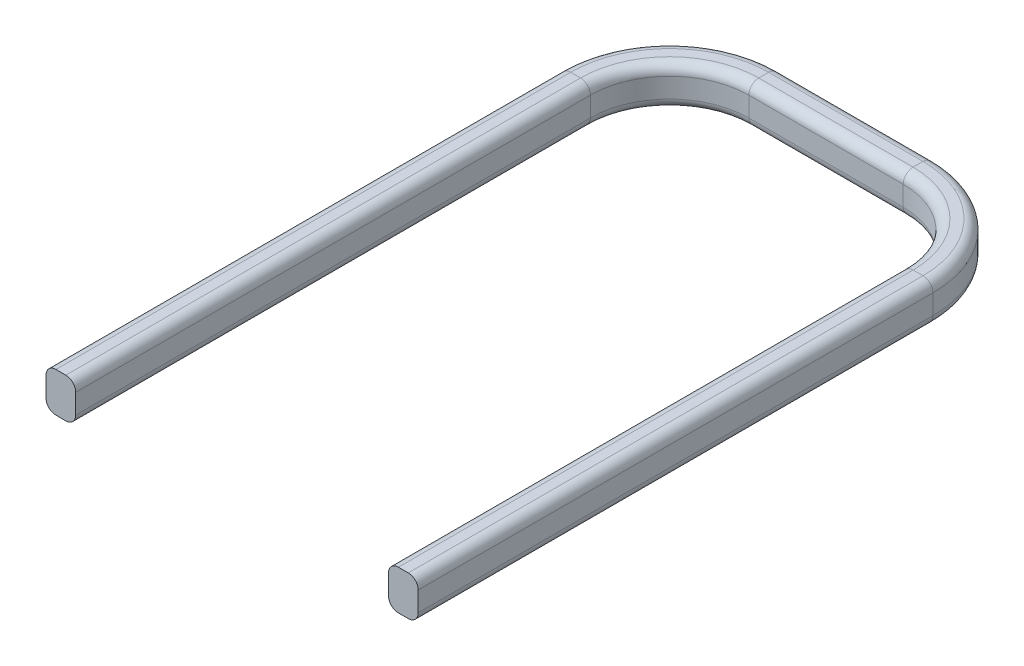
SolidWorks part; units mm, degrees
ref_plane "Front Plane" through (0, 0, 0) normal (0, 0, 1) x (1, 0, 0)
ref_plane "Top Plane" through (0, 0, 0) normal (0, 1, 0) x (1, 0, 0)
ref_plane "Right Plane" through (0, 0, 0) normal (1, 0, 0) x (0, 0, -1)
sketch "Sketch1" plane through (0, 0, 0) normal (0, 1, 0) x (1, 0, 0)
  line L0 (-3.95, 0) -> (-3.95, 13)
  line L1 (-1.95, 15) -> (1.95, 15)
  line L2 (3.95, 13) -> (3.95, 0)
  arc A0 (3.95, 13) -> (1.95, 15) centre (1.95, 13) ccw
  arc A1 (-1.95, 15) -> (-3.95, 13) centre (-1.95, 13) ccw
  point P4 (0, 0)
  point P5 (0, 0)
  point P7 (0, 0)
  point P8 (0, 0)
  point P9 (0, 15)
  point P10 (0, 0)
  point P15 (-3.95, 15)
  dimension "D3" = 2
  dimension "D1" = 3.95
  dimension "D2" = 15
sketch "Sketch2" plane through (0, 0, 0) normal (0, 0, 1) x (1, 0, 0)
  line L1 (-3.95, 0) -> (-4.7, 0)
  line L2 (-3.95, 0) -> (-3.95, 1)
  line L3 (-3.95, 1) -> (-4.7, 1)
  line L4 (-4.7, 0) -> (-4.7, 1)
  dimension "D1" = 1
  dimension "D2" = 0.75
sweep "Sweep1" add profiles "Sketch2" path "Sketch1"
fillet "Fillet1" radius 0.25 20 edges at (-4.7, 0, -6.5) (-3.8945, 0, -14.9445) (0, 0, -15.75) (3.8945, 0, -14.9445) (-3.95, 0, -6.5) (-3.3642, 0, -14.4142) (0, 0, -15) (3.3642, 0, -14.4142) (3.95, 1, -6.5) (3.3642, 1, -14.4142) (0, 1, -15) (-3.3642, 1, -14.4142) (4.7, 1, -6.5) (3.8945, 1, -14.9445) (0, 1, -15.75) (-3.8945, 1, -14.9445) (4.7, 0, -6.5) (3.95, 0, -6.5) (-3.95, 1, -6.5) (-4.7, 1, -6.5)
